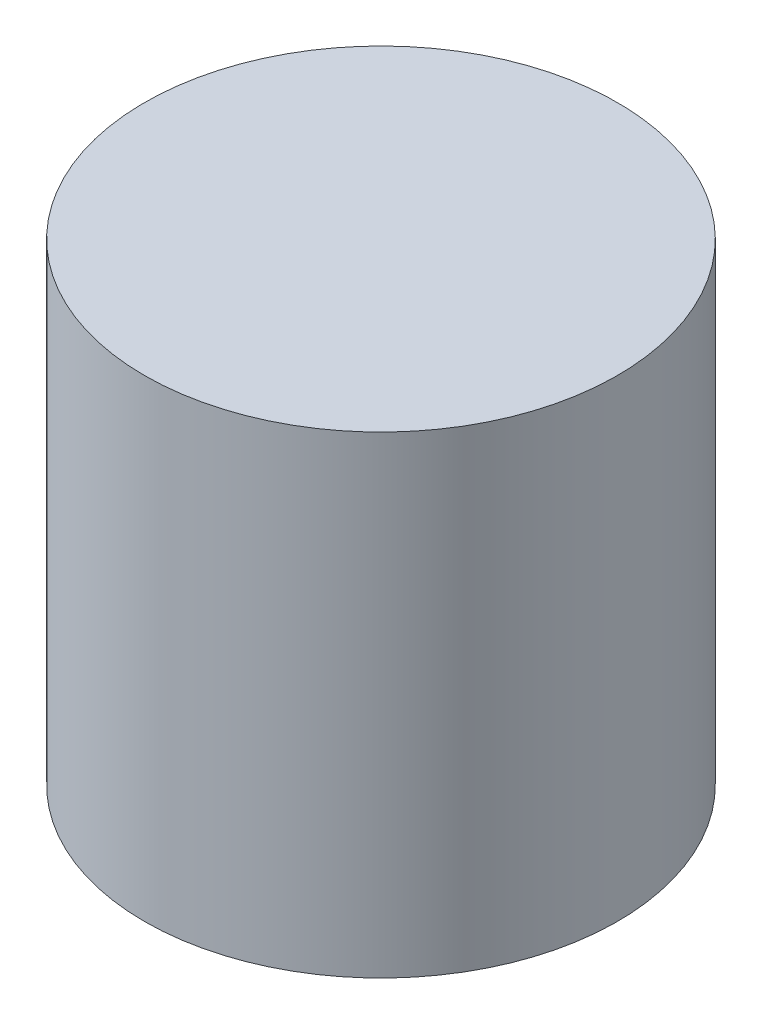
SolidWorks part; units mm, degrees
ref_plane "Front Plane" through (0, 0, 0) normal (0, 0, 1) x (1, 0, 0)
ref_plane "Top Plane" through (0, 0, 0) normal (0, 1, 0) x (1, 0, 0)
ref_plane "Right Plane" through (0, 0, 0) normal (1, 0, 0) x (0, 0, -1)
sketch "Sketch1" plane through (0, 0, 0) normal (0, 1, 0) x (1, 0, 0)
  circle A0 centre (0, 0) radius 3.175
  dimension "D1" = 6.35
extrude "Boss-Extrude1" add sketch "Sketch1" along normal blind 6.35 contours A0
sketch "Sketch2" plane through (0, 0, 0) normal (0, -1, 0) x (1, 0, 0)
  line L0 (-3.175, 0) -> (3.175, 0) construction
  line L1 (0, -2.5303) -> (0, 0) construction
  circle A0 centre (0, 0) radius 3.175 construction
  circle A1 centre (-1.9844, 0) radius 0.3969
  circle A2 centre (1.9844, 0) radius 0.3969
  dimension "D2" = 0.7937
  dimension "D3" = 1.9844
  dimension "D4" = 2.5303
extrude "Cut-Extrude1" cut sketch "Sketch2" against normal blind 2.1167 contours A2 | A1
